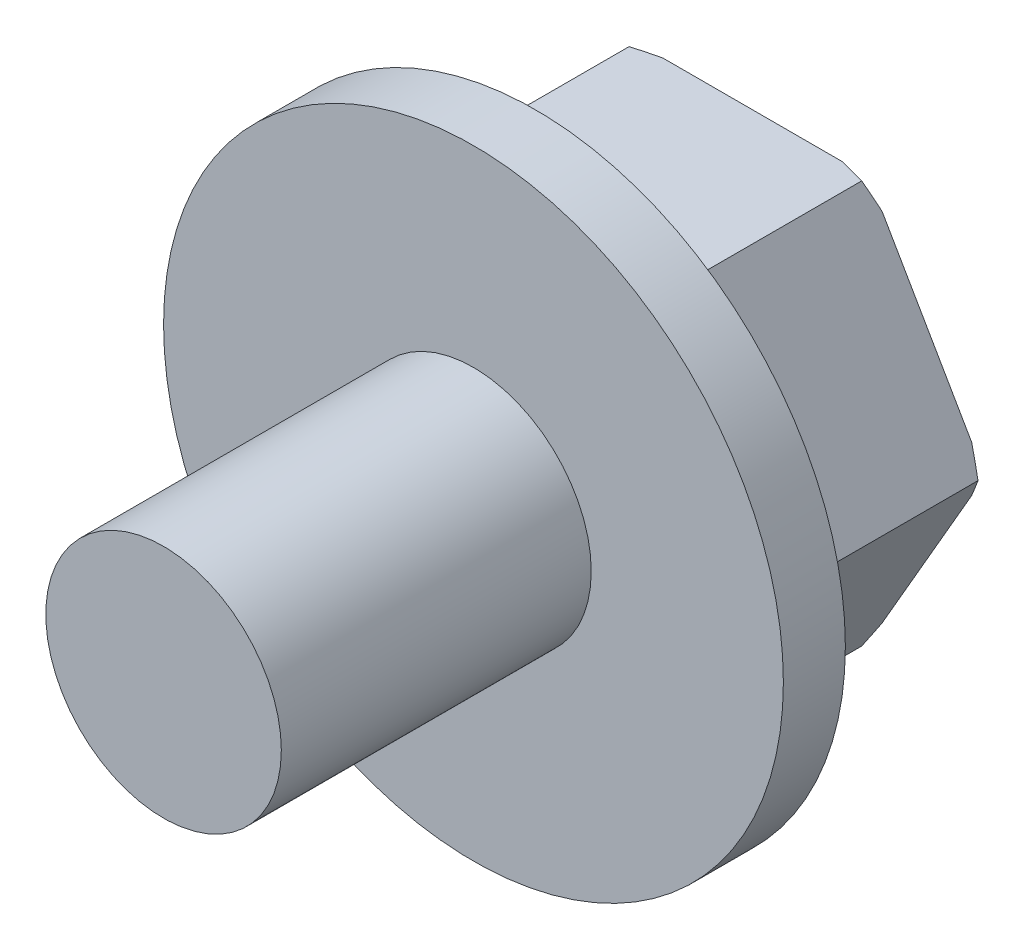
SolidWorks part; units mm, degrees
ref_plane "Alzado" through (0, 0, 0) normal (0, 0, 1) x (1, 0, 0)
ref_plane "Planta" through (0, 0, 0) normal (0, 1, 0) x (1, 0, 0)
ref_plane "Vista lateral" through (0, 0, 0) normal (1, 0, 0) x (0, 0, -1)
sketch "Croquis1" plane through (0, 0, 0) normal (0, 0, 1) x (1, 0, 0)
  circle A0 centre (0, 0) radius 3.8
  dimension "D1" = 7.6
extrude "Saliente-Extruir1" add sketch "Croquis1" along normal blind 10
sketch "Croquis3" plane through (0, 0, 0) normal (0, 0, -1) x (-1, 0, 0)
  circle A0 centre (0, 0) radius 10
  dimension "D1" = 20
extrude "Saliente-Extruir2" add sketch "Croquis3" along normal blind 2
sketch "Croquis4" plane through (0, 0, -2) normal (0, 0, -1) x (-1, 0, 0)
  line L0 (0, 0) -> (0, -6.5) construction
  line L1 (3.7528, -6.5) -> (7.5056, 0)
  line L2 (7.5056, 0) -> (3.7528, 6.5)
  line L3 (3.7528, 6.5) -> (-3.7528, 6.5)
  line L4 (-3.7528, 6.5) -> (-7.5056, 0)
  line L5 (-7.5056, 0) -> (-3.7528, -6.5)
  line L6 (-3.7528, -6.5) -> (3.7528, -6.5)
  circle A0 centre (0, 0) radius 6.5 construction
  dimension "D1" = 13
extrude "Saliente-Extruir3" add sketch "Croquis4" along normal blind 7
sketch "Croquis6" plane through (0, 0, -9) normal (0, 0, -1) x (-1, 0, 0)
  circle A0 centre (0, 0) radius 6
  dimension "D1" = 12
extrude "Cortar-Extruir6" cut sketch "Croquis6" against normal blind 0.5
sketch "Croquis7" plane through (0, 0, 0) normal (0, 1, 0) x (1, 0, 0)
  line L0 (0, 0) -> (0, 16.6618) construction
  line L1 (-5.5, 15.2) -> (-5.5, 9.9321)
  line L2 (-5.5, 9.9321) -> (-8.5, 8.2)
  line L3 (-8.5, 8.2) -> (-8.5, 15.2)
  line L4 (-8.5, 15.2) -> (-5.5, 15.2)
  line L5 (10, 2) -> (-10, 2) construction
  dimension "D1" = 60
  dimension "D2" = 6.2
  dimension "D3" = 3
  dimension "D4" = 7
  dimension "D5" = 5.5
revolve "Cortar-Revolución1" cut sketch "Croquis7" angle 360 about L0
